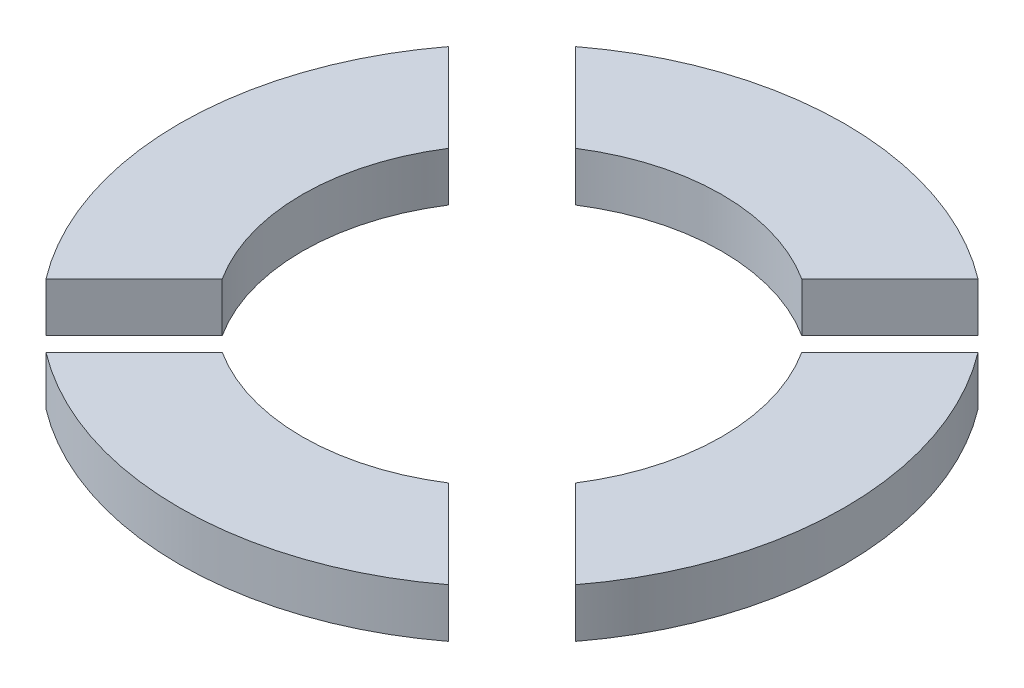
SolidWorks part; units mm, degrees
ref_plane "Front Plane" through (0, 0, 0) normal (0, 0, 1) x (1, 0, 0)
ref_plane "Top Plane" through (0, 0, 0) normal (0, 1, 0) x (1, 0, 0)
ref_plane "Right Plane" through (0, 0, 0) normal (1, 0, 0) x (0, 0, -1)
sketch "Sketch1" plane through (0, 0, 0) normal (0, 1, 0) x (1, 0, 0)
  line L0 (-0.4915, -0.647) -> (-0.2762, -0.4317)
  line L2 (0.4915, 0.647) -> (0.2762, 0.4317)
  line L4 (-0.647, 0.4915) -> (-0.4317, 0.2762)
  line L6 (-0.4915, 0.647) -> (-0.2762, 0.4317)
  line L8 (0, 0) -> (-0.4616, 0.4616) construction
  line L9 (0, 0) -> (0, -0.1061) construction
  line L10 (-0.4317, -0.2762) -> (-0.647, -0.4915)
  line L12 (0.4317, 0.2762) -> (0.647, 0.4915)
  line L13 (0.4317, -0.2762) -> (0.647, -0.4915)
  line L14 (0.2762, -0.4317) -> (0.4915, -0.647)
  line L18 (0, 0) -> (0, 0.5125) construction
  line L19 (-0.3838, 0.5394) -> (-0.5394, 0.3838) construction
  line L20 (0, 0) -> (-0.8125, 0) construction
  line L21 (0, 0) -> (0, -0.8125) construction
  line L22 (0, 0) -> (0.8125, 0) construction
  arc A8 (-0.4317, 0.2762) -> (-0.4317, -0.2762) centre (0, 0) ccw
  arc A9 (-0.647, 0.4915) -> (-0.647, -0.4915) centre (0, 0) ccw
  arc A10 (0.4915, 0.647) -> (-0.4915, 0.647) centre (0, 0) ccw
  arc A11 (0.2762, 0.4317) -> (-0.2762, 0.4317) centre (0, 0) ccw
  arc A12 (0.647, -0.4915) -> (0.647, 0.4915) centre (0, 0) ccw
  arc A13 (0.4317, -0.2762) -> (0.4317, 0.2762) centre (0, 0) ccw
  arc A14 (-0.4915, -0.647) -> (0.4915, -0.647) centre (0, 0) ccw
  arc A15 (-0.2762, -0.4317) -> (0.2762, -0.4317) centre (0, 0) ccw
  point P22 (-0.5125, 0)
  point P23 (-0.4616, 0.4616)
  point P25 (0, -0.5125)
  point P27 (0, 0.5125)
  dimension "D1" = 1.625
  dimension "D2" = 1.025
  dimension "D4" = 0.22
  dimension "D5" = 45
  dimension "D3" = 0.22
  dimension "D6" = 0.22
  dimension "D7" = 0.22
extrude "Boss-Extrude1" add sketch "Sketch1" along normal blind 0.12
equation "\"D3@Sketch1\"=\"D4@Sketch1\""
equation "\"D6@Sketch1\"=\"D4@Sketch1\""
equation "\"D7@Sketch1\"=\"D4@Sketch1\""
